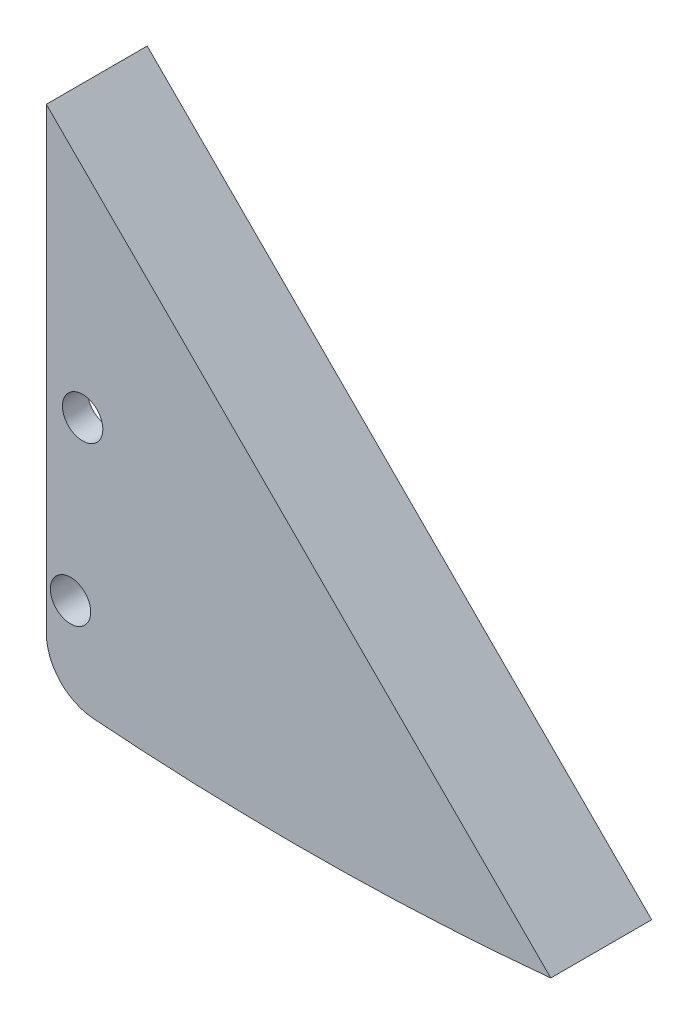
SolidWorks part; units mm, degrees
ref_plane "Alzado" through (0, 0, 0) normal (0, 0, 1) x (1, 0, 0)
ref_plane "Planta" through (0, 0, 0) normal (0, 1, 0) x (1, 0, 0)
ref_plane "Vista lateral" through (0, 0, 0) normal (1, 0, 0) x (0, 0, -1)
sketch "Croquis2" plane through (0, 0, 0) normal (0, 0, 1) x (1, 0, 0)
  line L0 (0, 0) -> (0, -25)
  line L2 (25, -25) -> (0, 0)
  spline S0 degree 2 poles (0, -25) (12.5951, -26.183) (25, -25) knots 0 0 0 0.592276 0.592276 0.592276
  dimension "D1" = 25
  dimension "D2" = 25
extrude "Saliente-Extruir1" add sketch "Croquis2" along normal blind 5
sketch "Croquis3" plane through (0, 0, 5) normal (0, 0, 1) x (1, 0, 0)
  line L4 (0, 0) -> (0, -25) construction
  circle A0 centre (1.2, -20.7) radius 1
  dimension "D3" = 2
  dimension "D1" = 4.3
  dimension "D2" = 1.2
extrude "Cortar-Extruir1" cut sketch "Croquis3" against normal blind 5
fillet "Redondeo2" radius 2.5 1 edges at (0, -25, 2.5)
sketch "Croquis4" plane through (0, 0, 0) normal (-1, 0, 0) x (0, 0, 1)
  line L1 (2.5012, -7.9) -> (2.5, 0) construction
  line L3 (3.7512, -7.9) -> (1.2512, -7.9)
  line L5 (3.7512, -7.9) -> (3.7512, -17.2)
  line L6 (3.7512, -17.2) -> (1.2512, -17.2)
  line L7 (1.2512, -17.2) -> (1.2512, -7.9)
  line L8 (5, 0) -> (0, 0) construction
  dimension "D1" = 2.5
  dimension "D2" = 9.3
  dimension "D3" = 7.9
extrude "Cortar-Extruir2" cut sketch "Croquis4" against normal blind 4.8
sketch "Croquis5" plane through (0, 0, 5) normal (0, 0, 1) x (1, 0, 0)
  line L0 (0, -12.55) -> (1.8, -12.55) construction
  line L2 (0, -7.9) -> (0, -17.2) construction
  circle A1 centre (1.8, -12.55) radius 1
  dimension "D1" = 1.8
  dimension "D2" = 2
extrude "Cortar-Extruir3" cut sketch "Croquis5" against normal through all both and the other way through all
